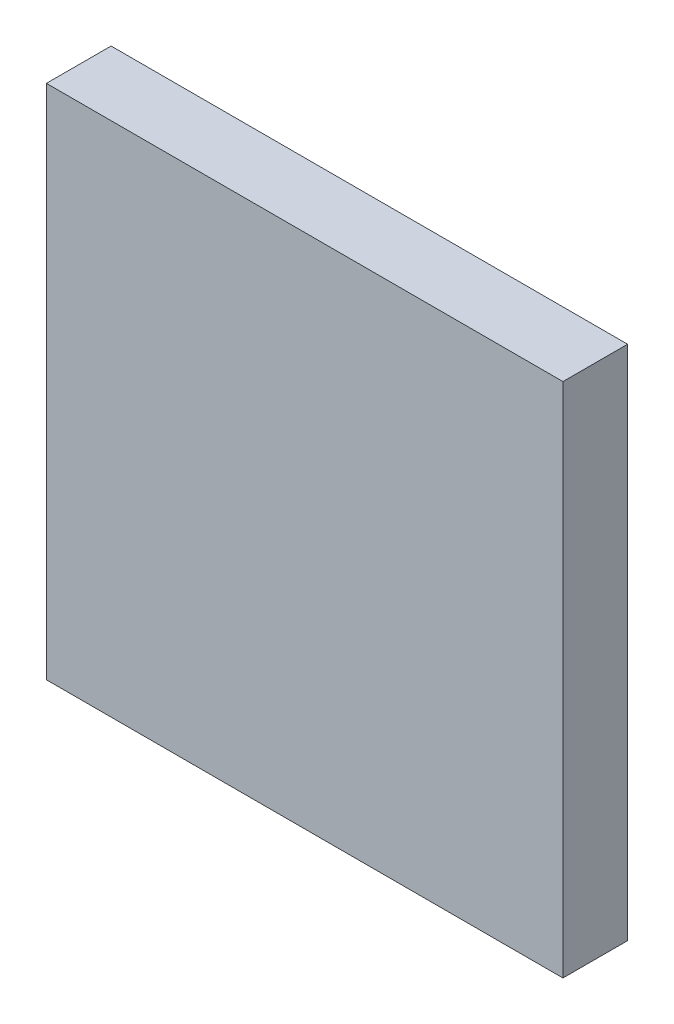
SolidWorks part; units mm, degrees
ref_plane "Front" through (0, 0, 0) normal (0, 0, 1) x (1, 0, 0)
ref_plane "Top" through (0, 0, 0) normal (0, 1, 0) x (1, 0, 0)
ref_plane "Right" through (0, 0, 0) normal (1, 0, 0) x (0, 0, -1)
sketch "Sketch1" plane through (0, 0, 0) normal (0, 0, 1) x (1, 0, 0)
  line L1 (-12.7, -12.7) -> (12.7, -12.7)
  line L2 (-12.7, -12.7) -> (-12.7, 12.7)
  line L3 (-12.7, 12.7) -> (12.7, 12.7)
  line L4 (12.7, -12.7) -> (12.7, 12.7)
  line L5 (-12.7, -12.7) -> (12.7, 12.7) construction
  line L6 (-12.7, 12.7) -> (12.7, -12.7) construction
  point P0 (0, 0)
  dimension "D1" = 25.4
  dimension "D2" = 25.4
extrude "Boss-Extrude1" add sketch "Sketch1" along normal blind 3.18
